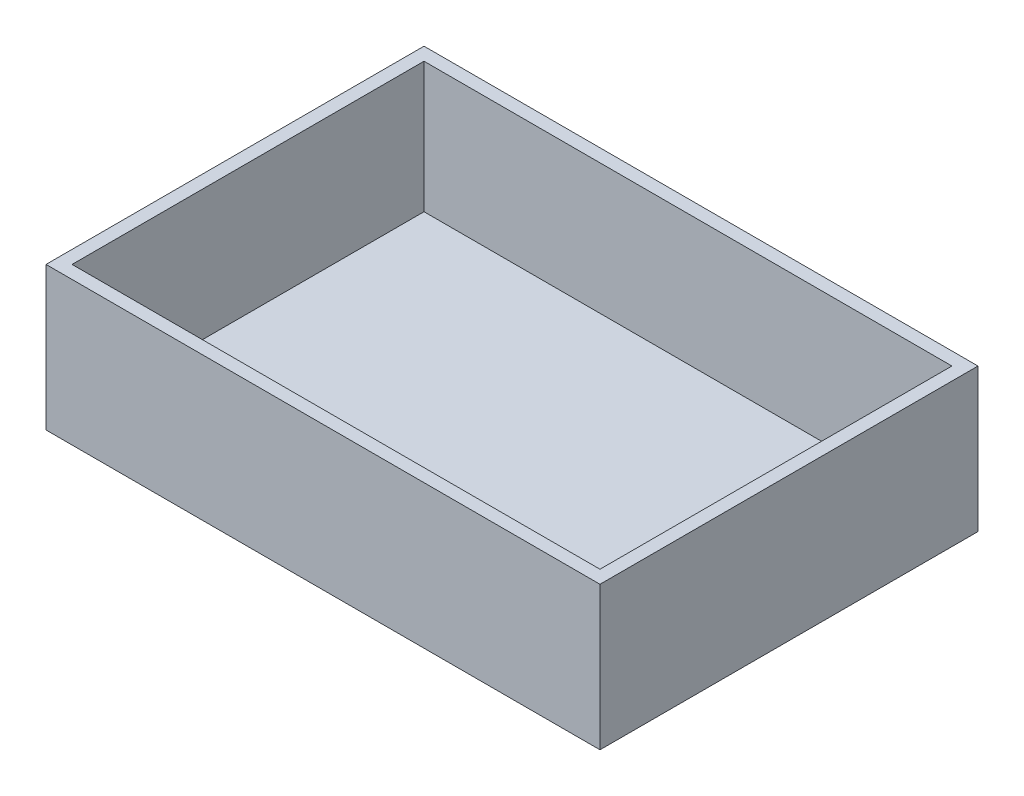
SolidWorks part; units mm, degrees
ref_plane "Front Plane" through (0, 0, 0) normal (0, 0, 1) x (1, 0, 0)
ref_plane "Top Plane" through (0, 0, 0) normal (0, 1, 0) x (1, 0, 0)
ref_plane "Right Plane" through (0, 0, 0) normal (1, 0, 0) x (0, 0, -1)
sketch "Sketch1" plane through (0, 0, 0) normal (0, 1, 0) x (1, 0, 0)
  line L0 (-212.5, -145) -> (212.5, -145)
  line L1 (-202.5, 135) -> (202.5, 135)
  line L2 (-202.5, 135) -> (-202.5, -135)
  line L3 (-202.5, -135) -> (202.5, -135)
  line L4 (202.5, 135) -> (202.5, -135)
  line L5 (-202.5, 135) -> (202.5, -135) construction
  line L6 (-202.5, -135) -> (202.5, 135) construction
  line L7 (212.5, 145) -> (212.5, -145)
  line L8 (-212.5, 145) -> (212.5, 145)
  line L9 (-212.5, 145) -> (-212.5, -145)
  point P0 (0, 0)
  dimension "D1" = 270
  dimension "D2" = 405
  dimension "D3" = 10
extrude "Boss-Extrude1" add sketch "Sketch1" along normal blind 100
sketch "Sketch2" plane through (0, 0, 0) normal (0, -1, 0) x (1, 0, 0)
  line L4 (-212.5, 145) -> (-212.5, -145)
  line L5 (-212.5, -145) -> (212.5, -145)
  line L6 (212.5, -145) -> (212.5, 145)
  line L7 (212.5, 145) -> (-212.5, 145)
  line L8 (-212.5, 145) -> (-212.5, -145)
  line L9 (-212.5, -145) -> (212.5, -145)
  line L10 (212.5, -145) -> (212.5, 145)
  line L11 (212.5, 145) -> (-212.5, 145)
  dimension "D1" = 0
extrude "Boss-Extrude2" add sketch "Sketch2" along normal blind 10
